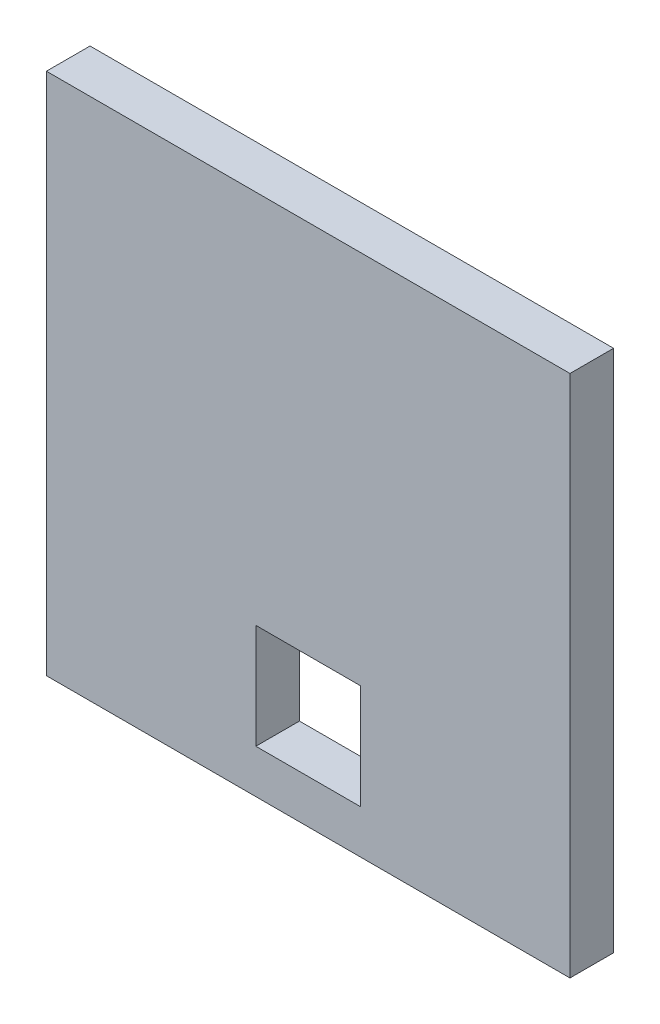
SolidWorks part; units mm, degrees
ref_plane "Front Plane" through (0, 0, 0) normal (0, 0, 1) x (1, 0, 0)
ref_plane "Top Plane" through (0, 0, 0) normal (0, 1, 0) x (1, 0, 0)
ref_plane "Right Plane" through (0, 0, 0) normal (1, 0, 0) x (0, 0, -1)
sketch "Sketch2" plane through (0, 0, 0) normal (0, 0, 1) x (1, 0, 0)
  line L1 (0, 0) -> (38.1, 0)
  line L2 (0, 0) -> (0, 38.1)
  line L3 (0, 38.1) -> (38.1, 38.1)
  line L4 (38.1, 0) -> (38.1, 38.1)
  dimension "D1" = 38.1
  dimension "D2" = 38.1
extrude "Boss-Extrude1" add sketch "Sketch2" along normal blind 3.175
sketch "Sketch8" plane through (0, 0, 3.175) normal (0, 0, 1) x (1, 0, 0)
  line L0 (0, 0) -> (38.1, 0) construction
  line L1 (15.24, 10.795) -> (22.86, 10.795)
  line L2 (15.24, 10.795) -> (15.24, 3.175)
  line L3 (15.24, 3.175) -> (22.86, 3.175)
  line L4 (22.86, 10.795) -> (22.86, 3.175)
  line L5 (38.1, 0) -> (38.1, 38.1) construction
  dimension "D1" = 7.62
  dimension "D2" = 7.62
  dimension "D3" = 3.175
  dimension "D4" = 15.24
extrude "Cut-Extrude2" cut sketch "Sketch8" against normal through all
